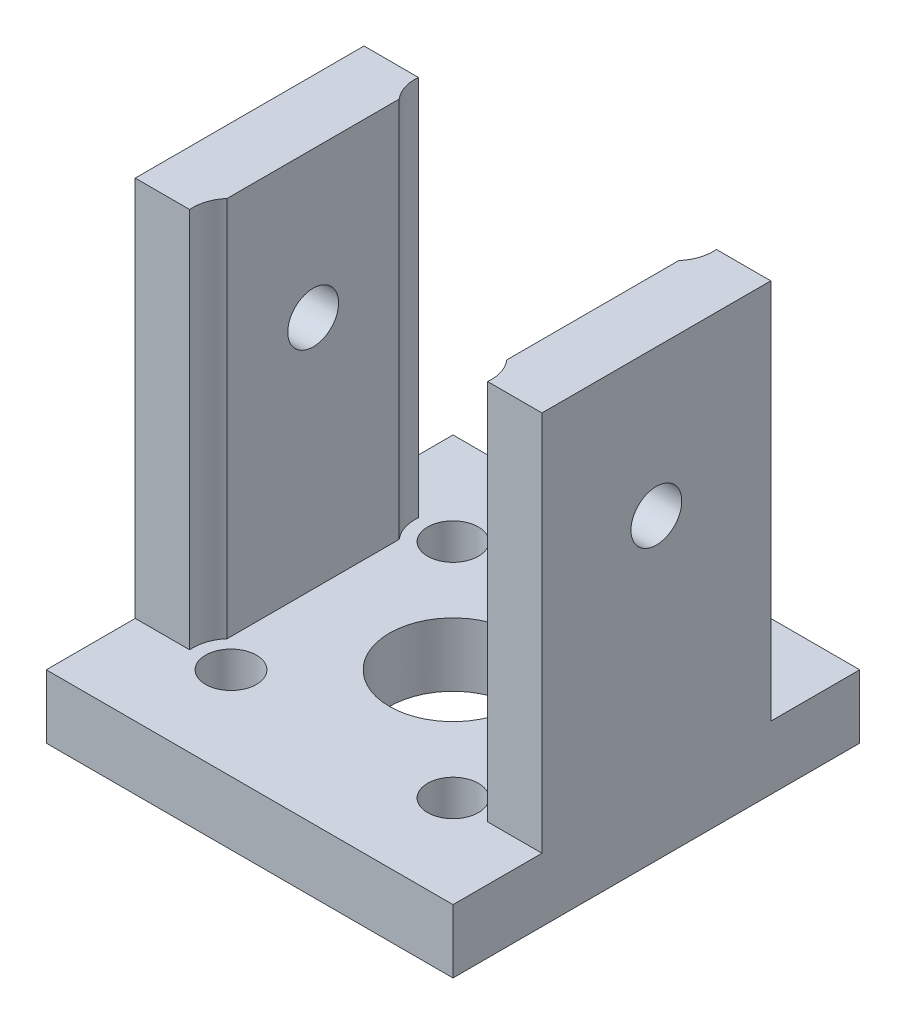
SolidWorks part; units mm, degrees
ref_plane "Front Plane" through (0, 0, 0) normal (0, 0, 1) x (1, 0, 0)
ref_plane "Top Plane" through (0, 0, 0) normal (0, 1, 0) x (1, 0, 0)
ref_plane "Right Plane" through (0, 0, 0) normal (1, 0, 0) x (0, 0, -1)
sketch "Sketch1" plane through (0, 0, 0) normal (0, 1, 0) x (1, 0, 0)
  line L1 (-16, 0) -> (16, 0)
  line L2 (-16, 0) -> (-16, -32)
  line L3 (-16, -32) -> (16, -32)
  line L4 (16, 0) -> (16, -32)
  dimension "D1" = 32
extrude "Boss-Extrude1" add sketch "Sketch1" along normal blind 5
sketch "Sketch2" plane through (0, 5, 0) normal (0, 1, 0) x (1, 0, 0)
  line L0 (-16, 0) -> (-16, -32) construction
  line L1 (-16, -7) -> (-11.7208, -7)
  line L2 (-16, -7) -> (-16, -25)
  line L3 (-16, -25) -> (-11.7212, -25)
  line L4 (-11, -9.2318) -> (-11, -22.7726)
  line L5 (0, 0) -> (0, -32) construction
  line L6 (16, 0) -> (-16, 0) construction
  line L7 (-16, -32) -> (16, -32) construction
  line L8 (16, -25) -> (11.7257, -25)
  line L9 (11, -9.237) -> (11, -22.7675)
  line L10 (16, -7) -> (11.7253, -7)
  line L11 (16, -7) -> (16, -25)
  circle A0 centre (-8.7328, -24.7328) radius 1.5 construction
  circle A1 centre (8.7328, -24.7328) radius 1.5 construction
  circle A2 centre (8.7328, -7.2672) radius 1.5 construction
  circle A3 centre (-8.7328, -7.2672) radius 1.5 construction
  circle A4 centre (-8.7328, -24.7328) radius 1.5 construction
  circle A5 centre (8.7328, -24.7328) radius 1.5 construction
  circle A6 centre (8.7328, -7.2672) radius 1.5 construction
  circle A7 centre (-8.7328, -7.2672) radius 1.5 construction
  arc A8 (-11.7208, -7) -> (-11, -9.2318) centre (-8.7328, -7.2672) ccw
  arc A9 (11, -9.237) -> (11.7253, -7) centre (8.7372, -7.2672) ccw
  arc A10 (11.7257, -25) -> (11, -22.7675) centre (8.7372, -24.7372) ccw
  arc A11 (-11, -22.7726) -> (-11.7212, -25) centre (-8.7328, -24.7372) ccw
  point P12 (-16, -16)
  point P13 (0, -16)
  dimension "D2" = 6
  dimension "D1" = 18
extrude "Boss-Extrude2" add sketch "Sketch2" along normal blind 30
sketch "Sketch3" plane through (0, 0, 0) normal (0, -1, 0) x (1, 0, 0)
  line L4 (-16, 32) -> (-16, 0)
  line L5 (-16, 0) -> (16, 0)
  line L6 (16, 0) -> (16, 32)
  line L7 (16, 32) -> (-16, 32)
  line L8 (-16, 32) -> (-16, 0) construction
  line L9 (-16, 0) -> (16, 0) construction
  line L10 (16, 0) -> (16, 32) construction
  line L11 (16, 32) -> (-16, 32) construction
  circle A0 centre (0, 16) radius 5
  circle A9 centre (-8.7328, 7.2672) radius 2
  circle A10 centre (-8.7328, 24.7328) radius 2
  circle A11 centre (8.7328, 24.7328) radius 2
  circle A12 centre (8.7328, 7.2672) radius 2
  point P10 (-16, 16)
  point P12 (0, 32)
  dimension "D1" = 0
  dimension "D2" = 10
extrude "Cut-Extrude1" cut sketch "Sketch3" against normal blind 10
sketch "Sketch4" plane through (-16, 0, 0) normal (-1, 0, 0) x (0, 0, 1)
  line L0 (7, 23.5) -> (25, 23.5) construction
  line L2 (7, 35) -> (25, 35) construction
  line L3 (25, 35) -> (25, 5) construction
  line L4 (7, 35) -> (7, 5) construction
  circle A0 centre (16, 23.5) radius 2
  dimension "D1" = 11.5
extrude "Cut-Extrude2" cut sketch "Sketch4" against normal through all
